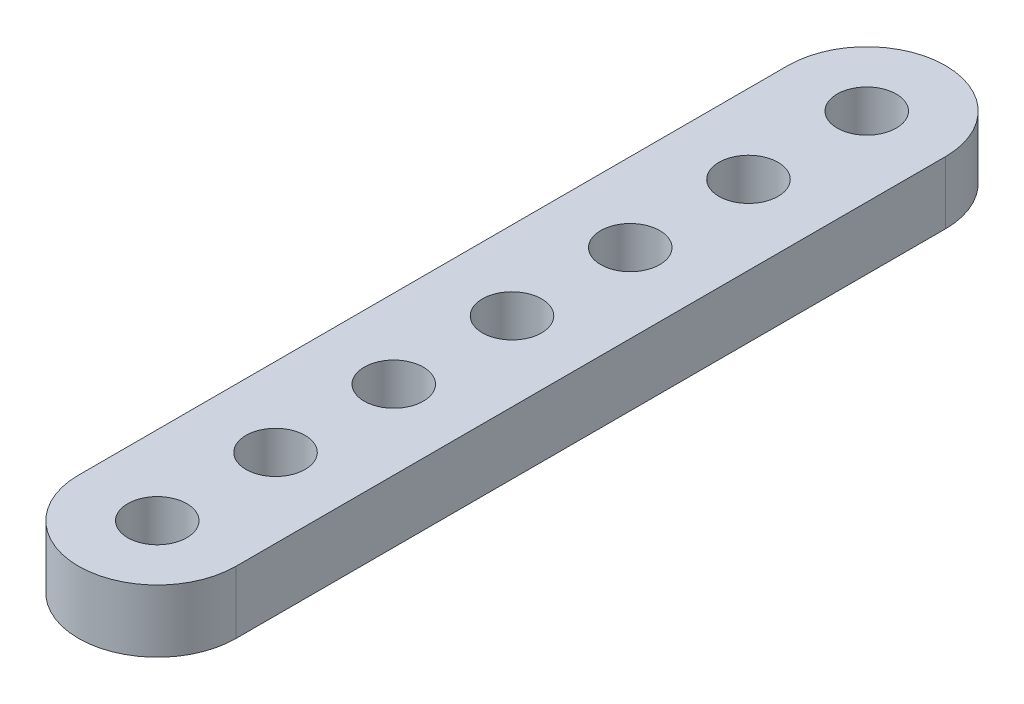
SolidWorks part; units mm, degrees
ref_plane "Front Plane" through (0, 0, 0) normal (0, 0, 1) x (1, 0, 0)
ref_plane "Top Plane" through (0, 0, 0) normal (0, 1, 0) x (1, 0, 0)
ref_plane "Right Plane" through (0, 0, 0) normal (1, 0, 0) x (0, 0, -1)
sketch "Sketch1" plane through (0, 0, 0) normal (0, 1, 0) x (1, 0, 0)
  line L2 (0, 0) -> (0, 36)
  line L4 (8, 0) -> (8, 36)
  line L5 (4, 4) -> (4, 0) construction
  arc A0 (8, 36) -> (0, 36) centre (4, 36) ccw
  arc A1 (0, 0) -> (8, 0) centre (4, 0) ccw
  circle A2 centre (4, 6) radius 1.5
  circle A3 centre (4, 0) radius 1.5
  circle A4 centre (4, 12) radius 1.5
  circle A5 centre (4, 18) radius 1.5
  circle A6 centre (4, 24) radius 1.5
  circle A7 centre (4, 30) radius 1.5
  circle A8 centre (4, 36) radius 1.5
  dimension "D3" = 7
  dimension "D4" = 3
  dimension "D1" = 8
  dimension "D2" = 0
  dimension "D5" = 0
extrude "Boss-Extrude1" add sketch "Sketch1" along normal blind 3.175
